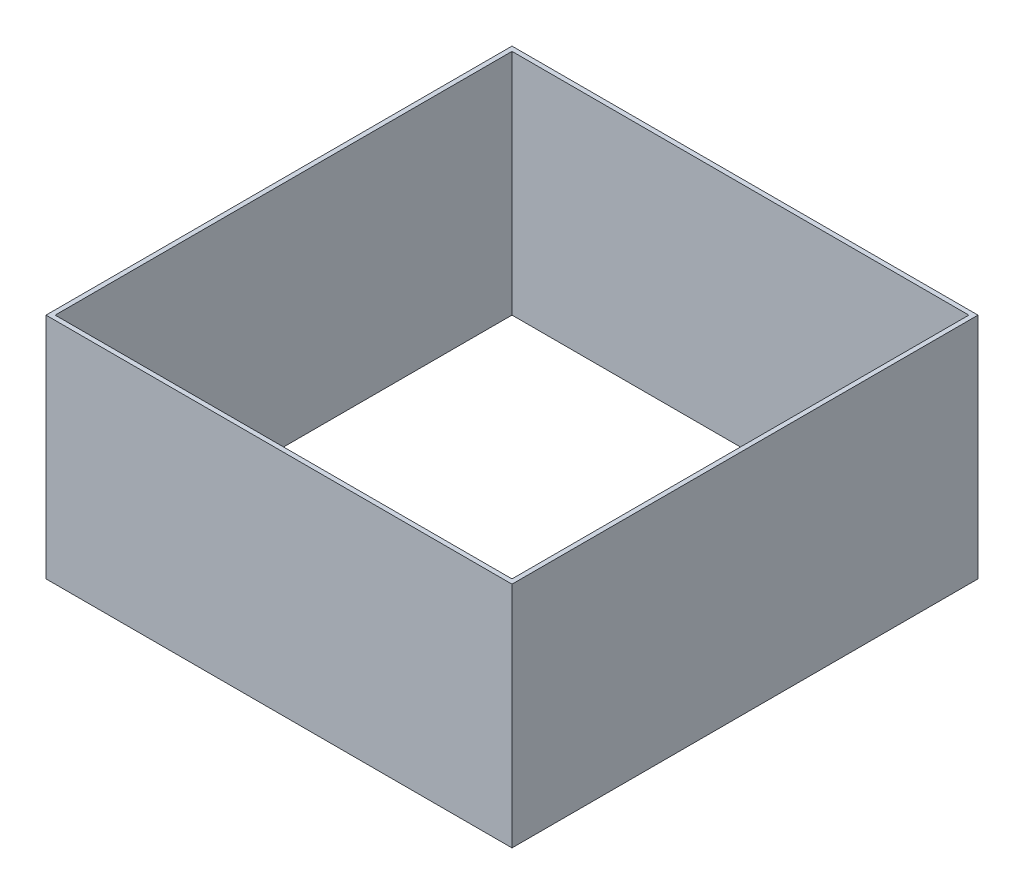
SolidWorks part; units mm, degrees
ref_plane "Alzado" through (0, 0, 0) normal (0, 0, 1) x (1, 0, 0)
ref_plane "Planta" through (0, 0, 0) normal (0, 1, 0) x (1, 0, 0)
ref_plane "Vista lateral" through (0, 0, 0) normal (1, 0, 0) x (0, 0, -1)
sketch "Croquis1" plane through (0, 0, 0) normal (0, 1, 0) x (1, 0, 0)
  line L1 (100, -100) -> (-100, -100)
  line L2 (100, -100) -> (100, 100)
  line L3 (100, 100) -> (-100, 100)
  line L4 (-100, -100) -> (-100, 100)
  line L5 (100, -100) -> (-100, 100) construction
  line L6 (100, 100) -> (-100, -100) construction
  line L7 (102, -102) -> (-102, -102)
  line L8 (102, -102) -> (102, 102)
  line L9 (102, 102) -> (-102, 102)
  line L10 (-102, -102) -> (-102, 102)
  line L11 (102, -102) -> (-102, 102) construction
  line L12 (102, 102) -> (-102, -102) construction
  point P0 (0, 0)
  point P5 (0, 0)
  dimension "D1" = 200
  dimension "D2" = 200
  dimension "D3" = 2
  dimension "D4" = 2
extrude "Saliente-Extruir1" add sketch "Croquis1" along normal blind 100
